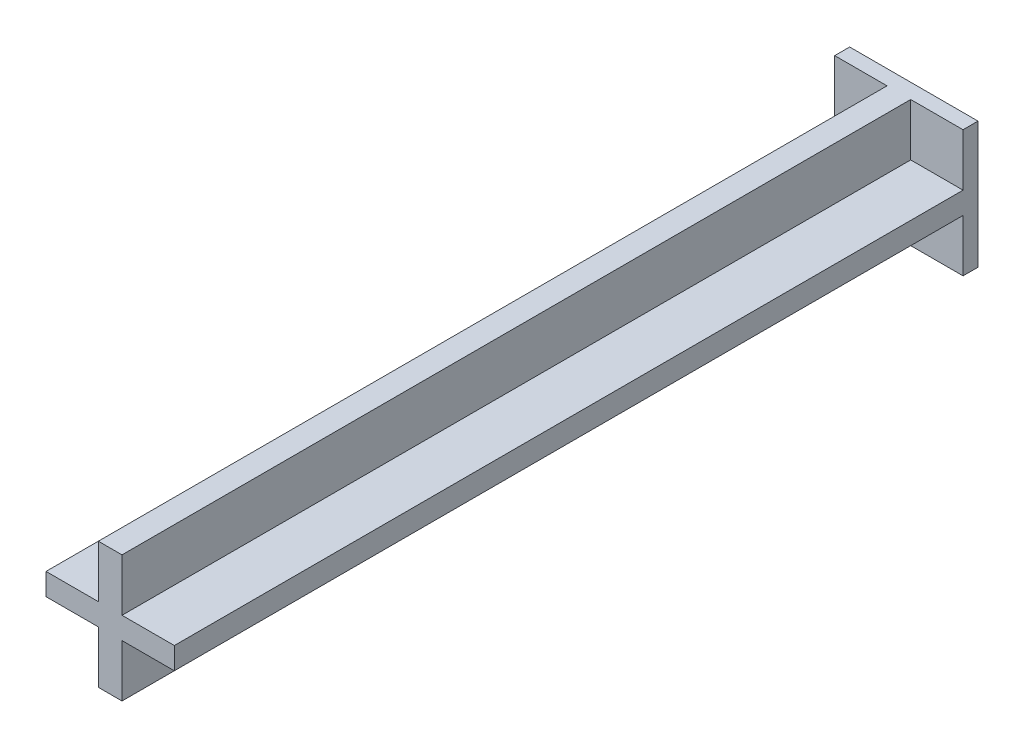
SolidWorks part; units mm, degrees
ref_plane "Front Plane" through (0, 0, 0) normal (0, 0, 1) x (1, 0, 0)
ref_plane "Top Plane" through (0, 0, 0) normal (0, 1, 0) x (1, 0, 0)
ref_plane "Right Plane" through (0, 0, 0) normal (1, 0, 0) x (0, 0, -1)
sketch "Sketch1" plane through (0, 0, 0) normal (0, 0, 1) x (1, 0, 0)
  line L1 (-109, -107.5) -> (109, -107.5)
  line L2 (-109, -107.5) -> (-109, 107.5)
  line L3 (-109, 107.5) -> (109, 107.5)
  line L4 (109, -107.5) -> (109, 107.5)
  line L5 (-109, -107.5) -> (109, 107.5) construction
  line L6 (-109, 107.5) -> (109, -107.5) construction
  point P0 (0, 0)
  dimension "D1" = 215
  dimension "D2" = 218
extrude "Boss-Extrude1" add sketch "Sketch1" along normal blind 1365 contours L3 L4 L1 L2
sketch "Sketch2" plane through (0, 0, 1365) normal (0, 0, 1) x (1, 0, 0)
  line L0 (0, 0) -> (173.0698, 0) construction
  line L1 (109, 107.5) -> (20.1, 107.5)
  line L2 (109, 107.5) -> (109, 18.6)
  line L3 (109, 18.6) -> (20.1, 18.6)
  line L4 (20.1, 107.5) -> (20.1, 18.6)
  line L5 (0, 0) -> (0, 126.0784) construction
  line L6 (-109, 18.6) -> (-20.1, 18.6)
  line L7 (-20.1, 107.5) -> (-20.1, 18.6)
  line L8 (-109, 107.5) -> (-20.1, 107.5)
  line L9 (-109, 107.5) -> (-109, 18.6)
  line L10 (109, -18.6) -> (20.1, -18.6)
  line L11 (20.1, -107.5) -> (20.1, -18.6)
  line L12 (109, -107.5) -> (20.1, -107.5)
  line L13 (109, -107.5) -> (109, -18.6)
  line L14 (-109, -107.5) -> (-109, -18.6)
  line L15 (-109, -107.5) -> (-20.1, -107.5)
  line L16 (-20.1, -107.5) -> (-20.1, -18.6)
  line L17 (-109, -18.6) -> (-20.1, -18.6)
  dimension "D1" = 88.9
extrude "Cut-Extrude1" cut sketch "Sketch2" against normal offset from surface (1339.6 mm away) 25.4 up to face at (0, 0, 0)
